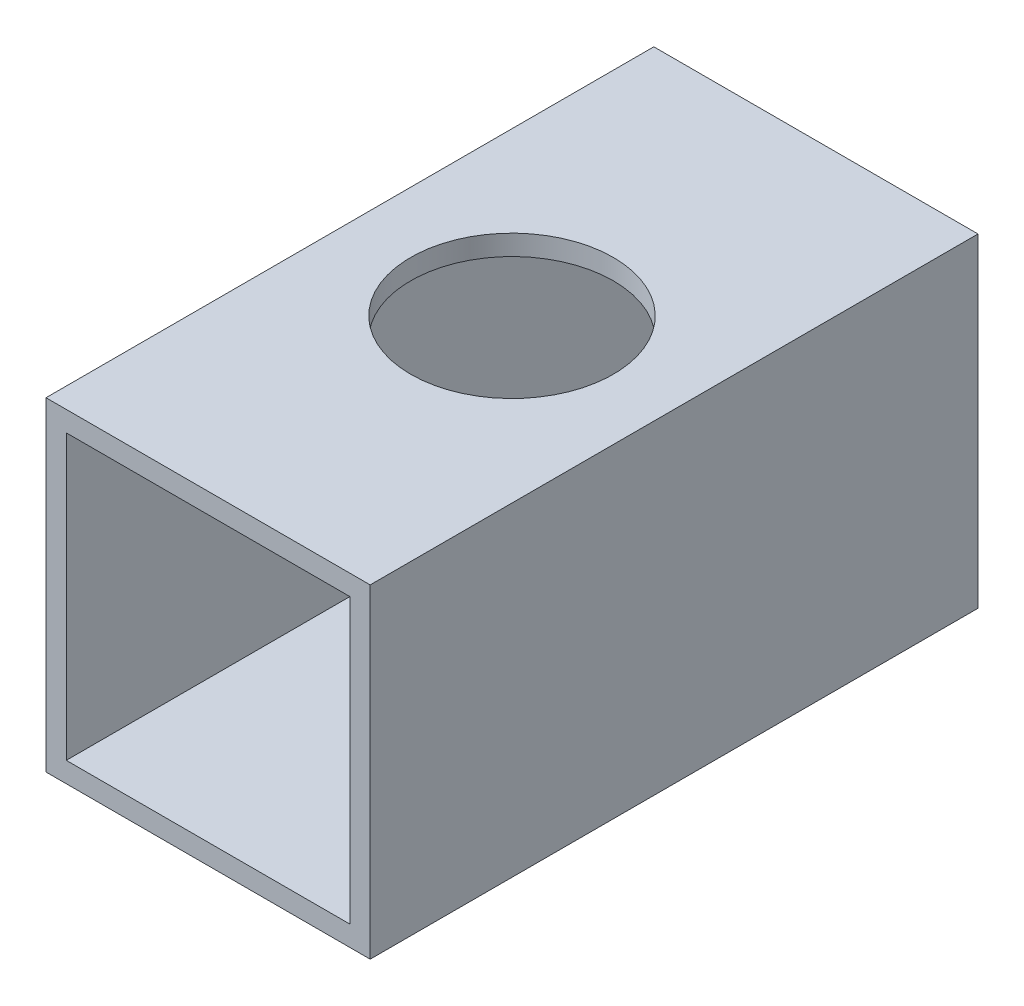
SolidWorks part; units mm, degrees
material "6061 Legierung"
ref_plane "Ebene vorne" through (0, 0, 0) normal (0, 0, 1) x (1, 0, 0)
ref_plane "Ebene oben" through (0, 0, 0) normal (0, 1, 0) x (1, 0, 0)
ref_plane "Ebene rechts" through (0, 0, 0) normal (1, 0, 0) x (0, 0, -1)
sketch "Skizze1" plane through (0, 0, 0) normal (0, 0, 1) x (1, 0, 0)
  line L0 (-8, 8) -> (8, 8)
  line L1 (-7, -7) -> (7, -7)
  line L2 (-7, -7) -> (-7, 7)
  line L3 (-7, 7) -> (7, 7)
  line L4 (7, -7) -> (7, 7)
  line L5 (-7, -7) -> (7, 7) construction
  line L6 (-7, 7) -> (7, -7) construction
  line L7 (8, -8) -> (8, 8)
  line L8 (-8, -8) -> (8, -8)
  line L9 (-8, -8) -> (-8, 8)
  point P0 (0, 0)
  dimension "D1" = 1
  dimension "D2" = 16
  dimension "D3" = 16
extrude "Aufsatz-Linear austragen1" add sketch "Skizze1" along normal mid plane 30
sketch "Skizze2" plane through (0, 8, 0) normal (0, 1, 0) x (1, 0, 0)
  circle A0 centre (0, 0) radius 2.5
  dimension "D1" = 5
extrude "Schnitt-Linear austragen1" cut sketch "Skizze2" against normal blind 30
sketch "Skizze3" plane through (0, 8, 0) normal (0, 1, 0) x (1, 0, 0)
  circle A0 centre (0, 0) radius 5
  dimension "D1" = 10
extrude "Schnitt-Linear austragen2" cut sketch "Skizze3" against normal blind 5
